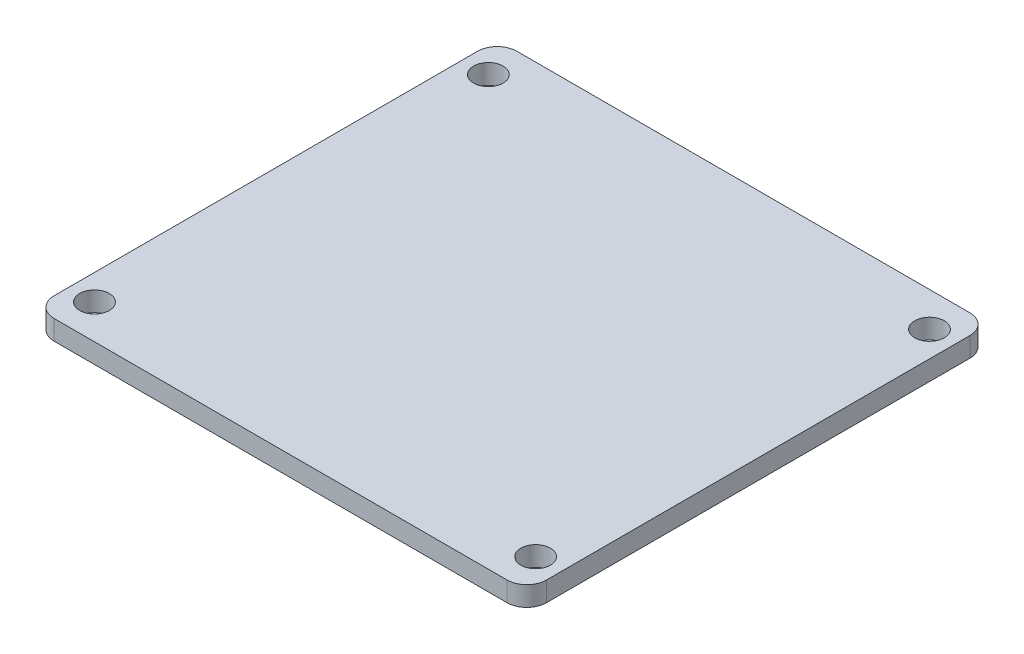
SolidWorks part; units mm, degrees
material "A-玻璃纤维"
ref_plane "前视基准面" through (0, 0, 0) normal (0, 0, 1) x (1, 0, 0)
ref_plane "上视基准面" through (0, 0, 0) normal (0, 1, 0) x (1, 0, 0)
ref_plane "右视基准面" through (0, 0, 0) normal (1, 0, 0) x (0, 0, -1)
sketch "草图1" plane through (0, 0, 0) normal (0, 1, 0) x (1, 0, 0)
  line L1 (-25, 23.5) -> (25, 23.5)
  line L2 (-25, 23.5) -> (-25, -23.5)
  line L3 (-25, -23.5) -> (25, -23.5)
  line L4 (25, 23.5) -> (25, -23.5)
  line L5 (0, -23.5) -> (0, 23.5) construction
  line L6 (-25, 0) -> (25, 0) construction
  circle A0 centre (-22.4, 20) radius 1.5
  circle A1 centre (22.4, 20) radius 1.5
  circle A2 centre (22.4, -20) radius 1.5
  circle A3 centre (-22.4, -20) radius 1.5
  point P0 (0, 0)
  dimension "D3" = 40
  dimension "D4" = 44.8
  dimension "D5" = 3
  dimension "D1" = 47
  dimension "D2" = 50
extrude "凸台-拉伸1" add sketch "草图1" along normal blind 2
fillet "圆角1" radius 2 4 edges at (-25, 1, 23.5) (-25, 1, -23.5) (25, 1, -23.5) (25, 1, 23.5)
sketch "草图2" plane through (0, 2, 0) normal (0, 1, 0) x (1, 0, 0)
  line L4 (-25, 21.5) -> (-25, -21.5)
  line L5 (-23, -23.5) -> (23, -23.5)
  line L6 (25, -21.5) -> (25, 21.5)
  line L7 (23, 23.5) -> (-23, 23.5)
  line L8 (-25, 21.5) -> (-25, -21.5)
  line L9 (-23, -23.5) -> (23, -23.5)
  line L10 (25, -21.5) -> (25, 21.5)
  line L11 (23, 23.5) -> (-23, 23.5)
  arc A4 (-25, -21.5) -> (-23, -23.5) centre (-23, -21.5) ccw
  arc A5 (23, -23.5) -> (25, -21.5) centre (23, -21.5) ccw
  arc A6 (25, 21.5) -> (23, 23.5) centre (23, 21.5) ccw
  arc A7 (-23, 23.5) -> (-25, 21.5) centre (-23, 21.5) ccw
  arc A8 (-25, -21.5) -> (-23, -23.5) centre (-23, -21.5) ccw
  arc A9 (23, -23.5) -> (25, -21.5) centre (23, -21.5) ccw
  arc A10 (25, 21.5) -> (23, 23.5) centre (23, 21.5) ccw
  arc A11 (-23, 23.5) -> (-25, 21.5) centre (-23, 21.5) ccw
  dimension "D1" = 0
surface "曲面-拉伸1" [suppressed] sketch "草图2" parameters "D1"=40
surface "曲面填充1" [suppressed]
